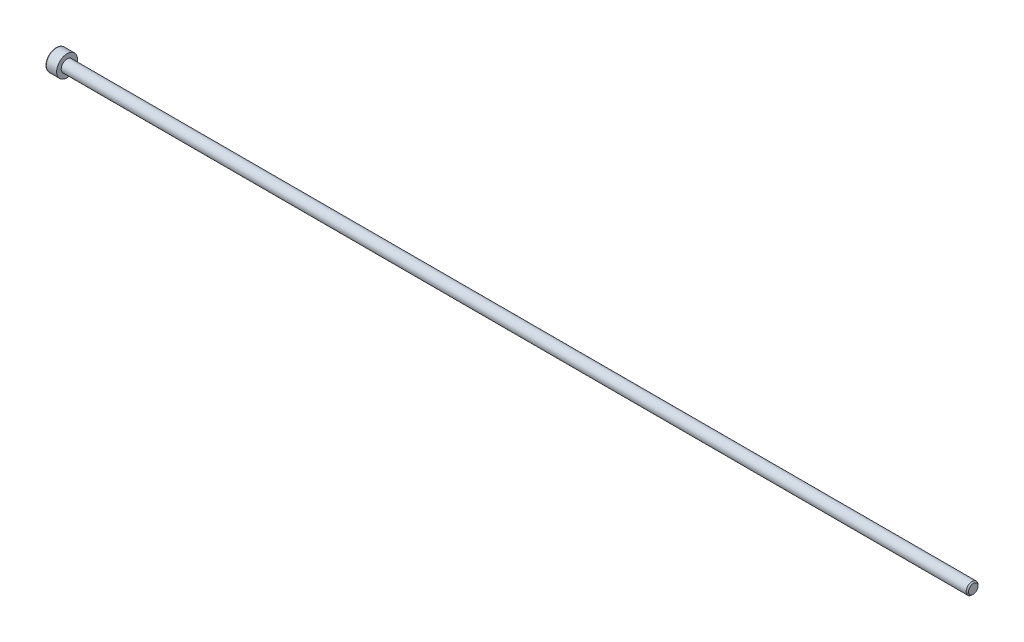
SolidWorks part; units mm, degrees
material "1023 Carbon Steel Sheet (SS)"
ref_plane "Ebene vorne" through (0, 0, 0) normal (0, 0, 1) x (1, 0, 0)
ref_plane "Ebene oben" through (0, 0, 0) normal (0, 1, 0) x (1, 0, 0)
ref_plane "Ebene rechts" through (0, 0, 0) normal (1, 0, 0) x (0, 0, -1)
ref_plane "Plane1" through (0, 0, 0) normal (0, 0, -1) x (-1, 0, 0)
sketch "Sketch1" plane through (0, 0, 0) normal (0, 0, -1) x (-1, 0, 0)
  line L0 (0, 1.5) -> (0, 0) construction
  line L1 (0, 0) -> (2.86, 0)
  line L2 (2.86, 0) -> (2.86, 2.66)
  line L3 (2.86, 2.66) -> (0, 2.66)
  line L4 (0, 0) -> (2.86, 0) construction
  line L5 (0, 0) -> (-230, 0)
  line L6 (-230, 0) -> (-230, 1.5)
  line L7 (-230, 1.5) -> (0, 1.5)
  line L8 (0, 2.66) -> (0, 1.5)
  dimension "D1" = 2.66
  dimension "D2" = 2.86
  dimension "D3" = 1.5
  dimension "D4" = 230
revolve "Revolve1" add sketch "Sketch1" angle 360 about L4
sketch "Sketch2" plane through (-2.86, 0, 0) normal (-1, 0, 0) x (0, 0, 1)
  line L0 (-1.25, -0.7217) -> (0, -1.4434)
  line L1 (0, -1.4434) -> (1.25, -0.7217)
  line L2 (1.25, -0.7217) -> (1.25, 0.7217)
  line L3 (1.25, 0.7217) -> (0, 1.4434)
  line L4 (0, 1.4434) -> (-1.25, 0.7217)
  line L5 (-1.25, 0.7217) -> (-1.25, -0.7217)
extrude "Cut-Extrude1" cut sketch "Sketch2" against normal blind 1.3
fillet "Fillet1" radius 0.266 1 edges at (-2.86, -2.66, 0)
chamfer "Chamfer2" distance 0.3065 angle 45 1 edges at (230, -1.5, 0)
